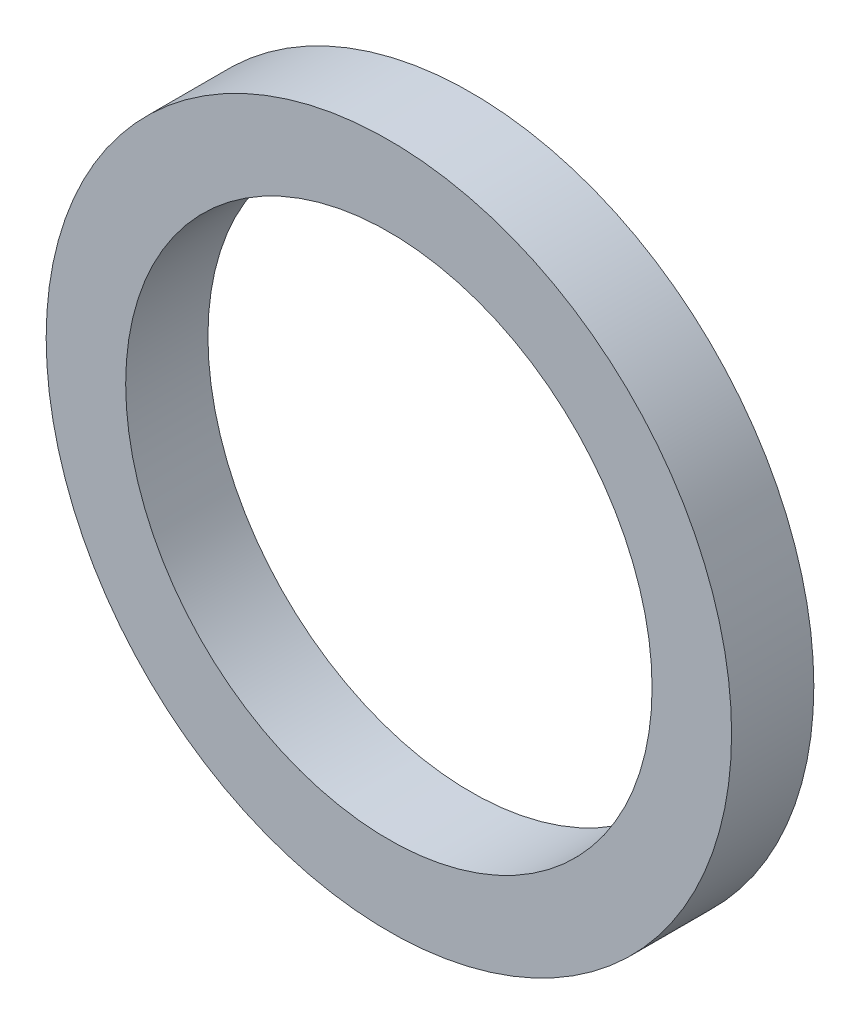
SolidWorks part; units mm, degrees
ref_plane "Front Plane" through (0, 0, 0) normal (0, 0, 1) x (1, 0, 0)
ref_plane "Top Plane" through (0, 0, 0) normal (0, 1, 0) x (1, 0, 0)
ref_plane "Right Plane" through (0, 0, 0) normal (1, 0, 0) x (0, 0, -1)
sketch "Sketch1" plane through (0, 0, 0) normal (0, 0, 1) x (1, 0, 0)
  circle A0 centre (0, 0) radius 31.75
  dimension "D2" = 63.5
extrude "Boss-Extrude1" add sketch "Sketch1" along normal blind 7.62
sketch "Sketch2" plane through (0, 0, 7.62) normal (0, 0, 1) x (1, 0, 0)
  line L1 (-31.75, 0) -> (31.75, 0)
  line L2 (-31.75, 0) -> (-31.75, -50.8)
  line L3 (-31.75, -50.8) -> (31.75, -50.8)
  line L4 (31.75, 0) -> (31.75, -50.8)
  circle A0 centre (0, 0) radius 31.75 construction
  dimension "D1" = 50.8
sketch "Sketch3" plane through (0, 0, 7.62) normal (0, 0, 1) x (1, 0, 0)
  circle A0 centre (0, 0) radius 24.384
  dimension "D1" = 48.768
extrude "Cut-Extrude1" cut sketch "Sketch3" against normal blind 7.62
equation "\"Foamcore\" = .1in"
equation "\"MDF\" = .3in"
equation "\"Gmaterial\"= \"MDF\""
equation "\"PVC-ID\" = \"1.590in\""
equation "\"PVC-OD\" = \"1.900in\""
equation "\"PVC-Sleeve-Width\" = \".51in\""
equation "\"D1@Boss-Extrude1\"=\"Gmaterial\""
